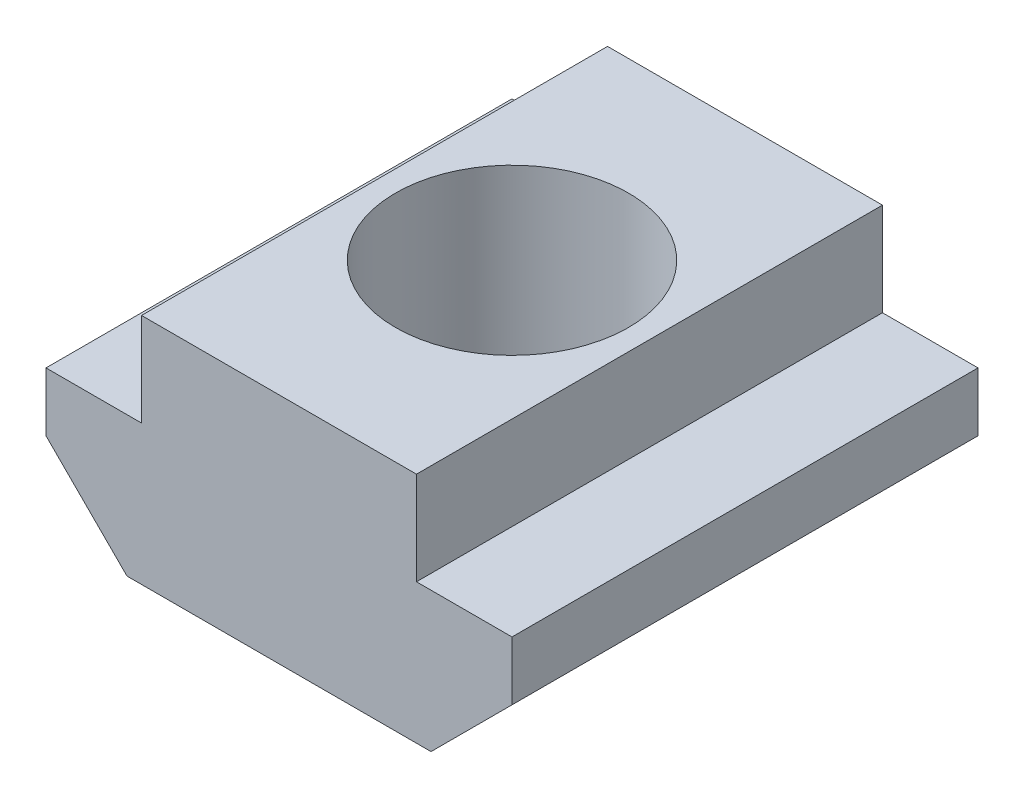
SolidWorks part; units mm, degrees
ref_plane "Plan de face" through (0, 0, 0) normal (0, 0, 1) x (1, 0, 0)
ref_plane "Plan de dessus" through (0, 0, 0) normal (0, 1, 0) x (1, 0, 0)
ref_plane "Plan de droite" through (0, 0, 0) normal (1, 0, 0) x (0, 0, -1)
sketch "Esquisse1" plane through (0, 0, 0) normal (0, 0, 1) x (1, 0, 0)
  line L0 (-10.5061, -2.0861) -> (-3.9814, -2.0861)
  line L1 (-3.9814, -2.0861) -> (-2.2437, -0.3484)
  line L2 (-2.2437, -0.3484) -> (-2.2437, 0.9139)
  line L3 (-2.2437, 0.9139) -> (-4.2937, 0.9139)
  line L4 (-4.2937, 0.9139) -> (-4.2937, 2.9139)
  line L5 (-4.2937, 2.9139) -> (-10.1937, 2.9139)
  line L6 (-10.1937, 2.9139) -> (-10.1937, 0.9139)
  line L7 (-10.1937, 0.9139) -> (-12.2437, 0.9139)
  line L8 (-12.2437, 0.9139) -> (-12.2437, -0.3484)
  line L9 (-12.2437, -0.3484) -> (-10.5061, -2.0861)
  point P2 (-7.2437, -2.0861)
  point P11 (-7.2437, 2.9139)
  dimension "D1" = 5.9
  dimension "D2" = 5
  dimension "D3" = 10
  dimension "D4" = 3
  dimension "D5" = 135
extrude "Boss.-Extru.1" add sketch "Esquisse1" along normal blind 10
sketch "Esquisse2" plane through (0, 2.9139, 0) normal (0, 1, 0) x (1, 0, 0)
  line L0 (-4.2937, -10) -> (-10.1937, -10) construction
  line L1 (-4.2937, -10) -> (-4.2937, 0) construction
  circle A0 centre (-7.2437, -5) radius 2.5
  point P5 (-7.2437, -10)
  point P8 (-4.2937, -5)
  dimension "D1" = 5
extrude "Enlèv. mat.-Extru.1" cut sketch "Esquisse2" against normal up to next
